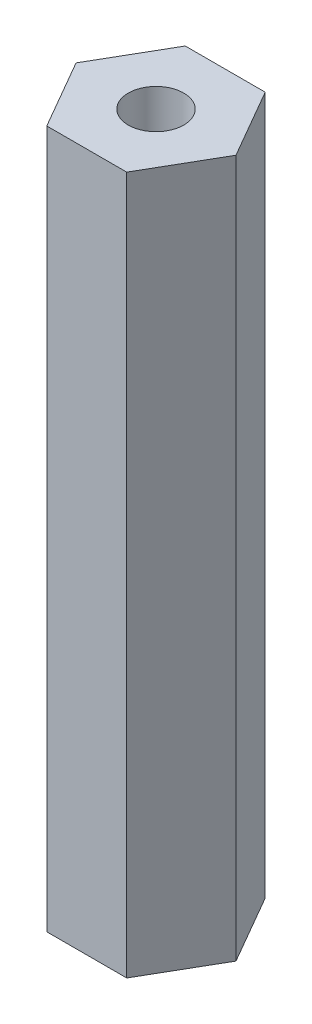
SolidWorks part; units mm, degrees
ref_plane "Front Plane" through (0, 0, 0) normal (0, 0, 1) x (1, 0, 0)
ref_plane "Top Plane" through (0, 0, 0) normal (0, 1, 0) x (1, 0, 0)
ref_plane "Right Plane" through (0, 0, 0) normal (1, 0, 0) x (0, 0, -1)
sketch "Sketch1" plane through (0, 0, 0) normal (0, 1, 0) x (1, 0, 0)
  line L1 (4.1061, 0) -> (2.0531, 3.556)
  line L2 (2.0531, 3.556) -> (-2.0531, 3.556)
  line L3 (-2.0531, 3.556) -> (-4.1061, 0)
  line L4 (-4.1061, 0) -> (-2.0531, -3.556)
  line L5 (-2.0531, -3.556) -> (2.0531, -3.556)
  line L6 (2.0531, -3.556) -> (4.1061, 0)
  line L7 (-16.1251, -3.556) -> (1.6251, -3.556) construction
  circle A0 centre (0, 0) radius 3.556 construction
  circle A1 centre (0, 0) radius 1.425
  dimension "D1" = 2.85
extrude "Boss-Extrude1" add sketch "Sketch1" along normal up to surface (35.84 mm away)
